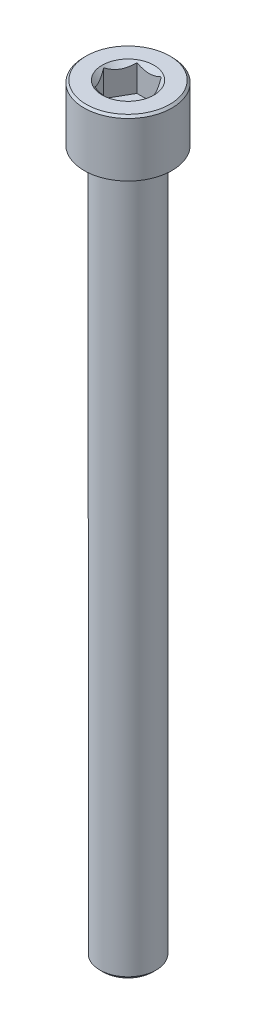
SolidWorks part; units mm, degrees
ref_plane "Płaszczyzna przednia" through (0, 0, 0) normal (0, 0, 1) x (1, 0, 0)
ref_plane "Płaszczyzna górna" through (0, 0, 0) normal (0, 1, 0) x (1, 0, 0)
ref_plane "Płaszczyzna prawa" through (0, 0, 0) normal (1, 0, 0) x (0, 0, -1)
sketch "Szkic1" plane through (0, 0, 0) normal (0, 0, 1) x (1, 0, 0)
  line L0 (0, 0) -> (0, 67.7826) construction
  line L1 (0, 0) -> (-4, 0)
  line L2 (-4, 0) -> (-4, 100)
  line L3 (-4, 100) -> (-6.25, 100)
  line L4 (-6.25, 100) -> (-6.25, 108)
  line L5 (-6.25, 108) -> (0, 108)
  line L6 (0, 108) -> (0, 0)
  dimension "D1" = 12.5
  dimension "D2" = 8
  dimension "D3" = 8
  dimension "D4" = 100
revolve "Obrót1" add sketch "Szkic1" angle 360 about L0
cosmetic thread "Oznaczenie gwintu1" parameters "D2"=6.619
sketch "Szkic2" plane through (0, 108, 0) normal (0, 1, 0) x (1, 0, 0)
  line L0 (0, 0) -> (5.3969, 0) construction
  line L1 (3.4641, 0) -> (1.7321, 3)
  line L2 (1.7321, 3) -> (-1.7321, 3)
  line L3 (-1.7321, 3) -> (-3.4641, 0)
  line L4 (-3.4641, 0) -> (-1.7321, -3)
  line L5 (-1.7321, -3) -> (1.7321, -3)
  line L6 (1.7321, -3) -> (3.4641, 0)
  circle A0 centre (0, 0) radius 3 construction
  dimension "D1" = 6
extrude "Wyciągnięcie1" cut sketch "Szkic2" against normal blind 4
chamfer "Sfazowanie1" distance 0.3 angle 45 1 edges at (0, 108, -6.25)
sketch "Szkic3" plane through (0, 108, 0) normal (0, 1, 0) x (1, 0, 0)
  circle A0 centre (0, 0) radius 3.6817
extrude "Wytnij-wyciągnięcie1" cut sketch "Szkic3" against normal blind 2 draft 45
chamfer "Sfazowanie2" distance 0.5 angle 45 1 edges at (0, 0, -4)
